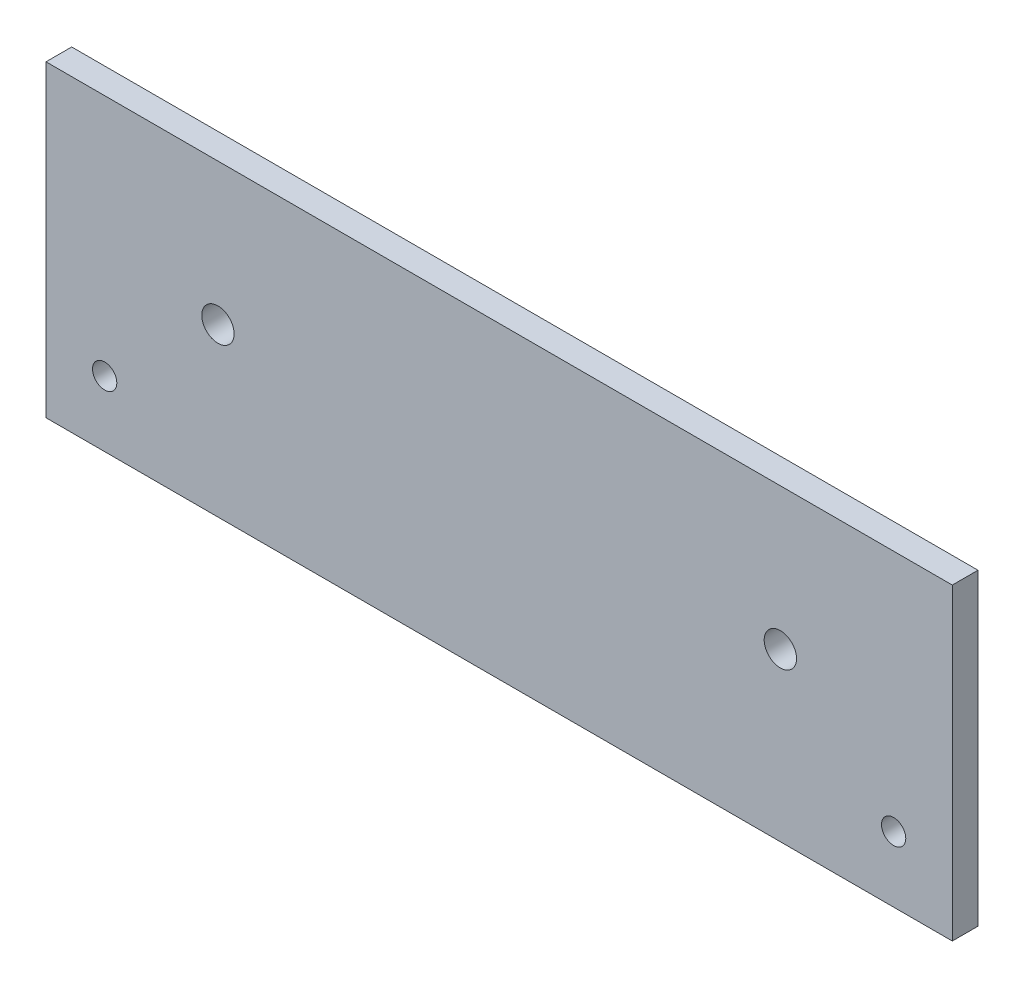
SolidWorks part; units mm, degrees
ref_plane "Front Plane" through (0, 0, 0) normal (0, 0, 1) x (1, 0, 0)
ref_plane "Top Plane" through (0, 0, 0) normal (0, 1, 0) x (1, 0, 0)
ref_plane "Right Plane" through (0, 0, 0) normal (1, 0, 0) x (0, 0, -1)
sketch "Sketch1" plane through (0, 0, 0) normal (0, 0, 1) x (1, 0, 0)
  line L0 (42.5, 41.2) -> (181.5, 41.2) construction
  line L1 (0, 0) -> (224, 0)
  line L2 (0, 0) -> (0, 76.2)
  line L3 (0, 76.2) -> (224, 76.2)
  line L4 (224, 0) -> (224, 76.2)
  line L5 (112, 85.8197) -> (112, -24.1253) construction
  line L6 (14.5, 16.2) -> (209.5, 16.2) construction
  circle A0 centre (42.5, 41.2) radius 4
  circle A1 centre (181.5, 41.2) radius 4
  circle A2 centre (14.5, 16.2) radius 3
  circle A3 centre (209.5, 16.2) radius 3
  dimension "D3" = 8
  dimension "D4" = 8
  dimension "D6" = 6
  dimension "D7" = 6
  dimension "D1" = 76.2
  dimension "D2" = 224
  dimension "D5" = 139
  dimension "D8" = 25
  dimension "D9" = 35
  dimension "D10" = 195
extrude "Boss-Extrude1" add sketch "Sketch1" along normal blind 6.35
equation "\"D4@Sketch1\"=\"D3@Sketch1\""
